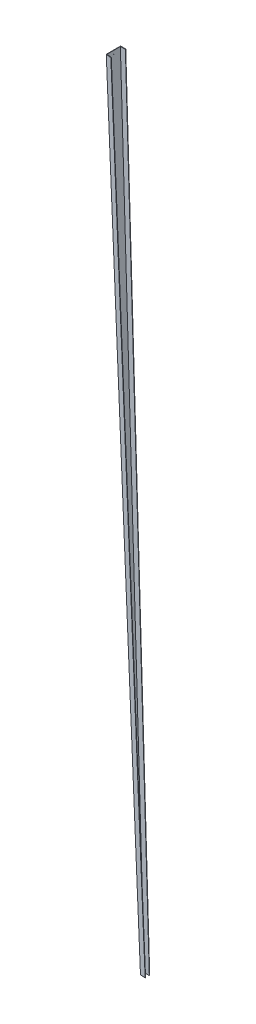
SolidWorks part; units mm, degrees
ref_plane "Front Plane" through (0, 0, 0) normal (0, 0, 1) x (1, 0, 0)
ref_plane "Top Plane" through (0, 0, 0) normal (0, 1, 0) x (1, 0, 0)
ref_plane "Right Plane" through (0, 0, 0) normal (1, 0, 0) x (0, 0, -1)
curve "Curve2"
  spline degree 3 poles (4000, 0, 3.36) (3933.7952, 0, 13.7836) (3801.3288, 0, 34.6398) (3535.8598, 0, 72.9041) (3203.3086, 0, 115.6254) (2803.4291, 0, 159.0217) (2402.8529, 0, 194.3246) (2001.6907, 0, 220.4636) (1599.3709, 0, 237.3526) (1263.2444, 0, 238.5562) (993.9739, 0, 228.1238) (792.1965, 0, 214.0116) (590.7612, 0, 192.5716) (423.6273, 0, 166.9066) (290.5285, 0, 139.3108) (190.9422, 0, 115.3098) (107.85, 0, 83.2401) (41.1412, 0, 57.7125) (-26.5303, 0, -2.7796) (51.7418, 0, -47.9035) (120.8588, 0, -63.3442) (208.0782, 0, -76.9163) (308.6135, 0, -84.9268) (442.4147, 0, -91.4528) (608.5618, 0, -94.255) (807.5001, 0, -93.1942) (1005.8652, 0, -89.7827) (1269.9834, 0, -83.4685) (1600.8258, 0, -74.8684) (1998.599, 0, -63.7434) (2397.4918, 0, -50.4963) (2796.9631, 0, -37.5709) (3197.1451, 0, -25.2391) (3531.1287, 0, -15.9133) (3798.838, 0, -8.6469) (3932.8931, 0, -5.1237) (4000, 0, -3.36) knots 0 0 0 0 0.02488 0.049781 0.099567 0.14934 0.199092 0.248839 0.298568 0.348561 0.373567 0.398591 0.423638 0.448742 0.461353 0.474029 0.486955 0.493558 0.502381 0.511191 0.517824 0.530564 0.54309 0.555505 0.580209 0.604805 0.629344 0.653862 0.702881 0.752206 0.801586 0.851045 0.900581 0.950217 0.975079 1 1 1 1
ref_plane "Plane1" through (0, -15000, 0) normal (0, 1, 0) x (1, 0, 0)
curve "Curve3"
  spline degree 3 poles (1250, -15000, 1.05) (1229.311, -15000, 4.3074) (1187.9152, -15000, 10.8249) (1104.9562, -15000, 22.7825) (1001.0339, -15000, 36.1329) (876.0716, -15000, 49.6943) (750.8915, -15000, 60.7264) (625.5283, -15000, 68.8949) (499.8034, -15000, 74.1727) (394.7639, -15000, 74.5488) (310.6168, -15000, 71.2887) (247.5614, -15000, 66.8786) (184.6129, -15000, 60.1786) (132.3835, -15000, 52.1583) (90.7902, -15000, 43.5346) (59.6694, -15000, 36.0343) (33.7031, -15000, 26.0125) (12.8566, -15000, 18.0352) (-8.2907, -15000, -0.8686) (16.1693, -15000, -14.9698) (37.7684, -15000, -19.7951) (65.0244, -15000, -24.0364) (96.4417, -15000, -26.5396) (138.2546, -15000, -28.579) (190.1756, -15000, -29.4547) (252.3438, -15000, -29.1232) (314.3329, -15000, -28.0571) (396.8698, -15000, -26.0839) (500.2581, -15000, -23.3964) (624.5622, -15000, -19.9198) (749.2162, -15000, -15.7801) (874.051, -15000, -11.7409) (999.1078, -15000, -7.8872) (1103.4777, -15000, -4.9729) (1187.1369, -15000, -2.7022) (1229.0291, -15000, -1.6012) (1250, -15000, -1.05) knots 0 0 0 0 0.02488 0.049781 0.099567 0.14934 0.199092 0.248839 0.298568 0.348561 0.373567 0.398591 0.423638 0.448742 0.461353 0.474029 0.486955 0.493558 0.502381 0.511191 0.517824 0.530564 0.54309 0.555505 0.580209 0.604805 0.629344 0.653862 0.702881 0.752206 0.801586 0.851045 0.900581 0.950217 0.975079 1 1 1 1
sketch "Sketch1" plane through (0, 0, 0) normal (0, 1, 0) x (1, 0, 0)
  line L17 (600, 93.4646) -> (600, -192.1843)
  line L18 (700, 89.6131) -> (699.9733, 81.6131)
  line L19 (699.3254, -197.7806) -> (700.1696, -189.8252)
  line L20 (604, 81.4705) -> (699.9733, 81.6131)
  line L21 (604, -178.6491) -> (700.1696, -189.8252)
  line L22 (604, 81.4705) -> (604, -178.6491)
  spline S1 degree 3 poles (600, 93.4646) (602.96, 93.4846) (672.1595, 93.9159) (807.5001, 93.1942) (1005.8652, 89.7827) (1269.9834, 83.4685) (1600.8258, 74.8684) (1998.599, 63.7434) (2331.9077, 52.6743) (2532.4261, 46.1441) (2600, 43.9641) knots 0.57911 0.57911 0.57911 0.57911 0.580209 0.604805 0.629344 0.653862 0.702881 0.752206 0.801586 0.826685 0.826685 0.826685 0.826685
  spline S2 degree 3 poles (2600, -176.5868) (2534.2697, -182.3468) (2334.9532, -198.7488) (2001.6907, -220.4636) (1599.3709, -237.3526) (1263.2444, -238.5562) (993.9739, -228.1238) (795.1742, -214.2199) (663.9659, -200.3608) (600, -192.1843) knots 0.174598 0.174598 0.174598 0.174598 0.199092 0.248839 0.298568 0.348561 0.373567 0.398591 0.42253 0.42253 0.42253 0.42253
  spline S3 degree 3 poles (2600, -170.5868) (2534.2697, -176.3468) (2334.9532, -192.7488) (2001.6907, -214.4636) (1599.3709, -231.3526) (1263.2444, -232.5562) (993.9739, -222.1238) (795.1742, -208.2199) (663.9659, -194.3608) (600, -186.1843) knots 0.174598 0.174598 0.174598 0.174598 0.199092 0.248839 0.298568 0.348561 0.373567 0.398591 0.42253 0.42253 0.42253 0.42253
  spline S4 degree 3 poles (600, 89.4646) (602.96, 89.4846) (672.1595, 89.9159) (807.5001, 89.1942) (1005.8652, 85.7827) (1269.9834, 79.4685) (1600.8258, 70.8684) (1998.599, 59.7434) (2331.9077, 48.6743) (2532.4261, 42.1441) (2600, 39.9641) knots 0.57911 0.57911 0.57911 0.57911 0.580209 0.604805 0.629344 0.653862 0.702881 0.752206 0.801586 0.826685 0.826685 0.826685 0.826685
  point P3 (1600, -234.76)
  point P20 (600, 81.4646)
  point P23 (600, -178.1843)
  dimension "D1" = 8
  dimension "D2" = 8
  dimension "D3" = 1000
  dimension "D4" = 100
  dimension "D5" = 100.0001
  dimension "D6" = 8
  dimension "D8" = 8
  dimension "4mm" = 4
sketch "Sketch2" plane through (0, -15000, 0) normal (0, 1, 0) x (1, 0, 0)
  line L16 (1387.4975, -136.9015) -> (1387.3602, -144.9003)
  line L18 (1287.5, -132.1898) -> (1287.5, -221.4551)
  line L20 (1387.0466, -224.9672) -> (1387.5763, -216.9847)
  line L21 (1291.5, -207.836) -> (1387.5763, -216.9847)
  line L22 (1291.5, -144.2183) -> (1387.3602, -144.9003)
  line L23 (1291.5, -144.2183) -> (1291.5, -207.836)
  line L24 (1600, -234.76) -> (1600, -138.035)
  spline S0 degree 3 poles (1287.5, -136.1898) (1288.425, -136.1836) (1310.0498, -136.0488) (1352.3438, -136.2743) (1414.3329, -137.3404) (1496.8698, -139.3136) (1558.7512, -140.9222) (1600, -142.035) knots 0.57911 0.57911 0.57911 0.57911 0.580209 0.604805 0.629344 0.653862 0.702881 0.702881 0.702881 0.702881 weights 1 1 1 1 1 1 1 1
  spline S2 degree 3 poles (1287.5, -132.1898) (1288.425, -132.1836) (1310.0498, -132.0488) (1352.3438, -132.2743) (1414.3329, -133.3404) (1496.8698, -135.3136) (1558.7512, -136.9222) (1600, -138.035) knots 0.57911 0.57911 0.57911 0.57911 0.580209 0.604805 0.629344 0.653862 0.702881 0.702881 0.702881 0.702881 weights 1 1 1 1 1 1 1 1
  spline S6 degree 3 poles (1600, -228.76) (1557.9238, -229.7201) (1494.7639, -229.9463) (1410.6168, -226.6862) (1348.4919, -222.3412) (1307.4893, -218.0103) (1287.5, -215.4551) knots 0.298568 0.298568 0.298568 0.298568 0.348561 0.373567 0.398591 0.42253 0.42253 0.42253 0.42253 weights 1 1 1 1 1 1 1
  spline S7 degree 3 poles (1600, -234.76) (1557.9238, -235.7201) (1494.7639, -235.9463) (1410.6168, -232.6862) (1348.4919, -228.3412) (1307.4893, -224.0103) (1287.5, -221.4551) knots 0.298568 0.298568 0.298568 0.298568 0.348561 0.373567 0.398591 0.42253 0.42253 0.42253 0.42253 weights 1 1 1 1 1 1 1
  point P17 (1287.5, -207.4551)
  point P18 (1600, -228.76)
  point P20 (1287.5, -144.1898)
  point P25 (1600, -234.76)
  point P26 (1600, -142.035)
  dimension "D2" = 6
  dimension "D3" = 8
  dimension "D4" = 8
  dimension "D5" = 8
  dimension "D6" = 8
  dimension "D7" = 4
  dimension "D8" = 312.5
  dimension "D9" = 4
  dimension "D10" = 6
  dimension "D11" = 4
  dimension "D12" = 86.725
  dimension "D13" = 100
  dimension "D14" = 13.3049
  dimension "D15" = 100
  dimension "D16" = 9.7928
  dimension "D17" = 89.2653
extrude "Boss-Extrude1" add sketch "Sketch1" against normal blind 6 contours S4 L17 S3 L19 L21 L22 L20 L18
extrude "Boss-Extrude2" add sketch "Sketch2" along normal blind 6 separate body
loft "Loft1" add section face at (650.8914, -6, 52.0188) section face at (1338.4073, -14994, 178.976)
hole_wizard "Ø4.0mm Dowel Hole1" positions "Sketch3" profile "Sketch4" hole size "Ø4.0" standard "JIS"
sketch "Sketch3" plane through (604.76, -22.5677, -62.9537) normal (0.9989, 0.0458, 0) x (-0.0458, 0.9989, 0)
  point P0 (-43.4148, 111.6597)
  point P1 (-43.4148, 151.6597)
  point P2 (-43.4148, 191.6597)
  point P3 (-43.4148, 71.6597)
  point P4 (-43.4148, 31.6597)
sketch "Sketch4" plane through (606.7493, -65.9369, 48.706) normal (0, 0, 1) x (-0.0458, 0.9989, 0)
  line L0 (0, 0) -> (0, 691.0556)
  line L1 (0, 691.0556) -> (2, 691.0556)
  line L2 (2, 691.0556) -> (2, 0)
  line L3 (2, 0) -> (0, 0)
  line L4 (0, -6.35) -> (0, 107.95) construction
  dimension "Thru Hole Dia." = 4
  dimension "Thru Hole Depth" = 691.0556
